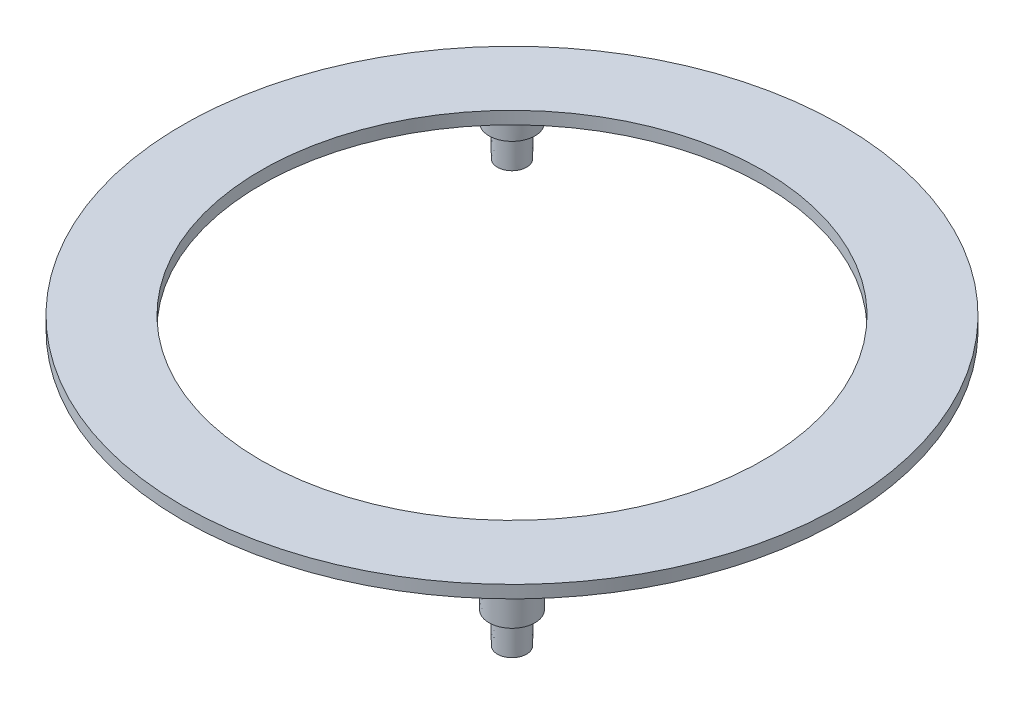
SolidWorks part; units mm, degrees
ref_plane "Front Plane" through (0, 0, 0) normal (0, 0, 1) x (1, 0, 0)
ref_plane "Top Plane" through (0, 0, 0) normal (0, 1, 0) x (1, 0, 0)
ref_plane "Right Plane" through (0, 0, 0) normal (1, 0, 0) x (0, 0, -1)
sketch "Sketch1" plane through (0, 0, 0) normal (0, 1, 0) x (1, 0, 0)
  circle A0 centre (0, 1.5306) radius 10.5
  circle A1 centre (0, 1.5306) radius 8
  dimension "D1" = 21
  dimension "D2" = 16
  dimension "D3" = 1.5306
extrude "Boss-Extrude1" add sketch "Sketch1" along normal blind 0.4
sketch "Sketch2" plane through (0, 0, 0) normal (0, 1, 0) x (1, 0, 0)
  line L0 (0, 1.5306) -> (-6.7175, -5.1869) construction
  line L1 (0, 1.5306) -> (0, -4.7232) construction
  circle A0 centre (-6.7175, -5.1869) radius 0.75
  point P13 (0, 0)
  dimension "D2" = 1.5
  dimension "D1" = 9.5
  dimension "D3" = 45
extrude "Boss-Extrude2" add sketch "Sketch2" against normal blind 1
sketch "Sketch3" plane through (0, -1, 0) normal (0, -1, 0) x (1, 0, 0)
  circle A0 centre (-6.7175, 5.1869) radius 0.5
  dimension "D1" = 1
extrude "Boss-Extrude3" add sketch "Sketch3" along normal blind 1
pattern_circular "CirPattern1" count 4 over 360 about axis through (0, 0, -1.5306) along (0, 1, 0) of "Boss-Extrude2", "Boss-Extrude3"
sketch "Sketch4" plane through (0, 0.4, 0) normal (0, 1, 0) x (1, 0, 0)
  line L0 (-0.75, 12.0038) -> (-0.75, 11.001) construction
  line L1 (0, -1.045) -> (0, 1.045) construction
  line L2 (0.75, 12.0038) -> (0.75, 11.001) construction
  circle A0 centre (0, 1.5306) radius 9.5 construction
  circle A1 centre (0, 1.5306) radius 10.5 construction
  circle A2 centre (0, 1.5306) radius 10.5 construction
  dimension "D1" = 19
  dimension "D3" = 1.5
sketch "Sketch5" plane through (0, 0.4, 0) normal (0, 1, 0) x (1, 0, 0)
  line L0 (-0.75, 12.0038) -> (-0.75, 11.001) construction
  line L1 (-0.75, 12.0038) -> (-0.75, 11.001)
  line L2 (0.75, 12.0038) -> (0.75, 11.001) construction
  line L3 (0.75, 12.0038) -> (0.75, 11.001)
  circle A0 centre (0, 1.5306) radius 10.5 construction
  arc A1 (0.75, 12.0038) -> (-0.75, 12.0038) centre (0, 1.5306) ccw
  circle A2 centre (0, 1.5306) radius 9.5 construction
  arc A3 (0.75, 11.001) -> (-0.75, 11.001) centre (0, 1.5306) ccw
draft "Draft1" type of draft neutral plane draft angle 1 faces to draft 8 face at (7.4675, -1, 5.1869) face at (6.2175, -2, 5.1869) face at (6.7175, -1, -8.9982) face at (6.7175, -2, -7.7482) face at (-7.4675, -1, -8.2482) face at (-6.2175, -2, -8.2482) face at (-6.7175, -1, 5.9369) face at (-6.7175, -2, 4.6869) neutral plane through (0, 0, -1.5306) neutral plane normal (0, -1, 0) parameters "D1"=1
